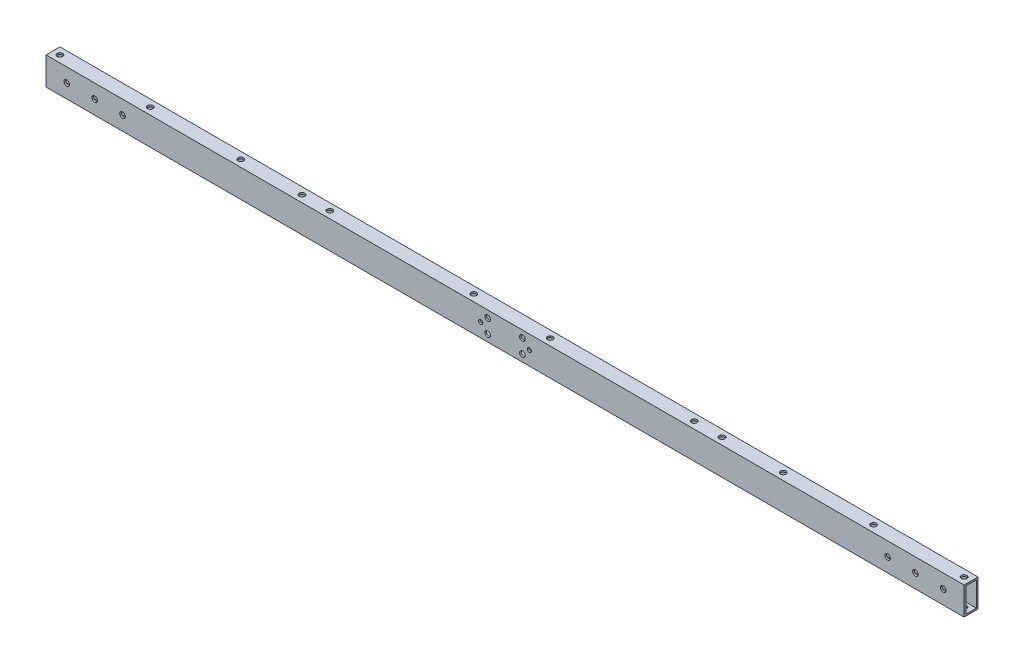
SolidWorks part; units mm, degrees
material "5052-H34"
ref_plane "正面" through (0, 0, 0) normal (0, 0, 1) x (1, 0, 0)
ref_plane "平面" through (0, 0, 0) normal (0, 1, 0) x (1, 0, 0)
ref_plane "右側面" through (0, 0, 0) normal (1, 0, 0) x (0, 0, -1)
sketch "ｽｹｯﾁ1" plane through (0, 0, 0) normal (1, 0, 0) x (0, 0, -1)
  line L1 (-5, 10) -> (5, 10)
  line L2 (-5, 10) -> (-5, -10)
  line L3 (-5, -10) -> (5, -10)
  line L4 (5, 10) -> (5, -10)
  line L5 (-5, 10) -> (5, -10) construction
  line L6 (-5, -10) -> (5, 10) construction
  point P0 (0, 0)
  dimension "D1" = 10
  dimension "D2" = 20
extrude "押し出し-薄板1" add sketch "ｽｹｯﾁ1" along normal blind 660 thin
sketch "ｽｹｯﾁ2" plane through (0, 10, 0) normal (0, 1, 0) x (1, 0, 0)
  line L0 (330, 5) -> (330, -5) construction
  line L1 (660, 5) -> (0, 5) construction
  line L2 (660, -5) -> (0, -5) construction
  line L3 (0, 0) -> (135, 0) construction
  line L4 (0, 5) -> (0, -5) construction
  line L5 (135, 0) -> (199, 0) construction
  line L6 (330, 0) -> (357.5, 0) construction
  circle A0 centre (5, 0) radius 2
  circle A1 centre (70, 0) radius 2
  circle A2 centre (135, 0) radius 2
  circle A3 centre (525, 0) radius 2
  circle A4 centre (590, 0) radius 2
  circle A5 centre (655, 0) radius 2
  circle A6 centre (199, 0) radius 2
  circle A7 centre (179, 0) radius 2
  circle A8 centre (481, 0) radius 2
  circle A9 centre (461, 0) radius 2
  circle A10 centre (357.5, 0) radius 2
  circle A11 centre (302.5, 0) radius 2
  dimension "D1" = 4
  dimension "D5" = 4
  dimension "D8" = 4
  dimension "D2" = 5
  dimension "D3" = 65
  dimension "D4" = 65
  dimension "D6" = 20
  dimension "D7" = 302
  dimension "D9" = 55
extrude "ｶｯﾄ - 押し出し1" cut sketch "ｽｹｯﾁ2" against normal through all
sketch "ｽｹｯﾁ3" plane through (0, 0, 5) normal (0, 0, 1) x (1, 0, 0)
  line L0 (330, 10) -> (330, -10) construction
  line L1 (660, 10) -> (0, 10) construction
  line L2 (660, -10) -> (0, -10) construction
  line L3 (330, 0) -> (347.5, 0) construction
  line L4 (347.5, 0) -> (342.5, 0) construction
  line L5 (342.5, 0) -> (342.5, 5) construction
  line L6 (660, 0) -> (504.5, 0) construction
  line L7 (660, 10) -> (660, -10) construction
  line L9 (0, 0) -> (50000, 0) construction
  line L10 (0, 10) -> (0, -10) construction
  circle A0 centre (347.5, 0) radius 1.5
  circle A1 centre (312.5, 0) radius 1.5
  circle A2 centre (342.5, 5) radius 2
  circle A3 centre (342.5, -5) radius 2
  circle A4 centre (317.5, -5) radius 2
  circle A5 centre (317.5, 5) radius 2
  circle A12 centre (15, 0) radius 2
  circle A13 centre (35, 0) radius 2
  circle A14 centre (55, 0) radius 2
  circle A15 centre (605, 0) radius 2
  circle A16 centre (625, 0) radius 2
  circle A17 centre (645, 0) radius 2
  dimension "D1" = 3
  dimension "D3" = 4
  dimension "D9" = 15
  dimension "D10" = 20
  dimension "D11" = 20
  dimension "D12" = 4
  dimension "D2" = 35
  dimension "D4" = 10
  dimension "D5" = 25
extrude "ｶｯﾄ - 押し出し2" cut sketch "ｽｹｯﾁ3" against normal through all
